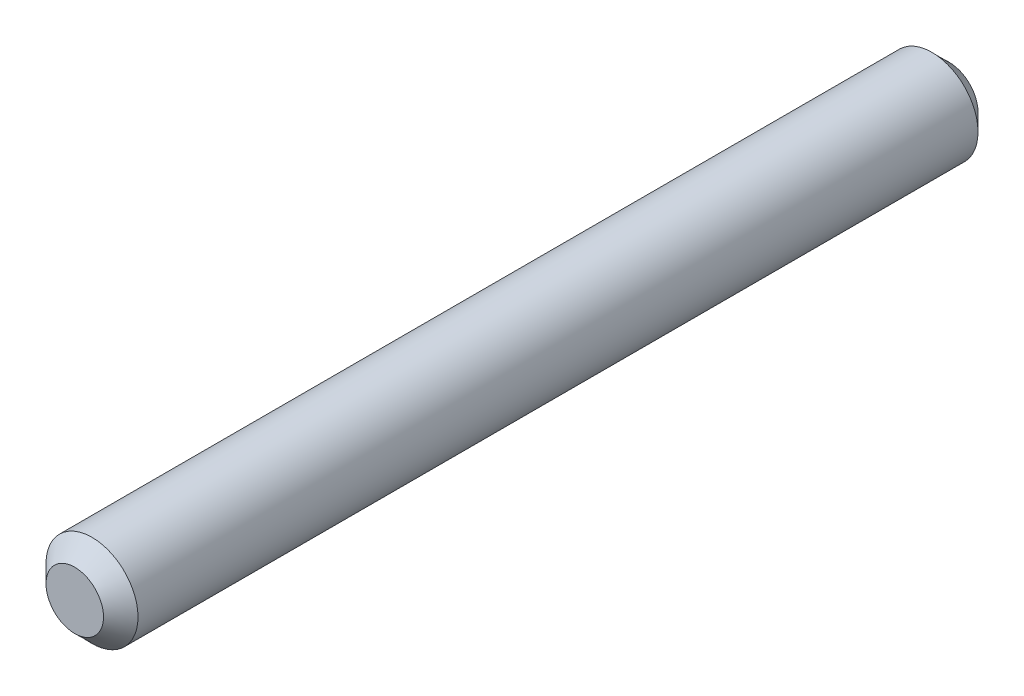
SolidWorks part; units mm, degrees
ref_plane "Front Plane" through (0, 0, 0) normal (0, 0, 1) x (1, 0, 0)
ref_plane "Top Plane" through (0, 0, 0) normal (0, 1, 0) x (1, 0, 0)
ref_plane "Right Plane" through (0, 0, 0) normal (1, 0, 0) x (0, 0, -1)
sketch "Sketch1" plane through (0, 0, 0) normal (0, 0, 1) x (1, 0, 0)
  circle A0 centre (0, 0) radius 4
  dimension "D1" = 8
extrude "Boss-Extrude1" add sketch "Sketch1" along normal blind 76.03
chamfer "Chamfer1" distance 1.5 angle 45 2 edges at (4, 0, 76.03) (4, 0, 0)
